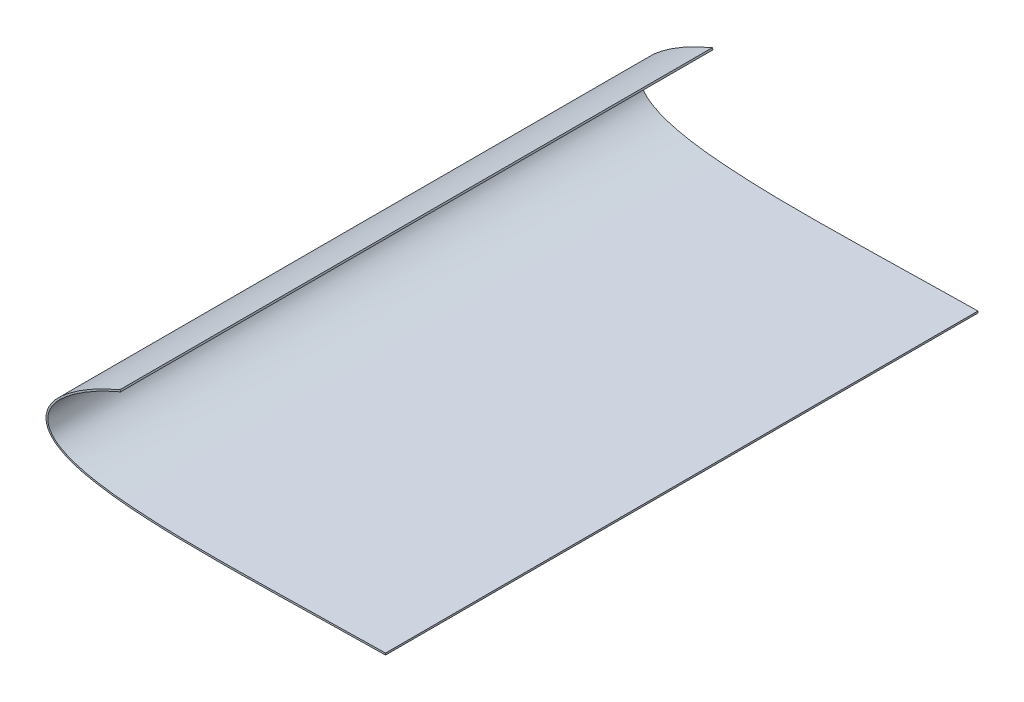
SolidWorks part; units mm, degrees
ref_plane "Front Plane" through (0, 0, 0) normal (0, 0, 1) x (1, 0, 0)
ref_plane "Top Plane" through (0, 0, 0) normal (0, 1, 0) x (1, 0, 0)
ref_plane "Right Plane" through (0, 0, 0) normal (1, 0, 0) x (0, 0, -1)
curve "ImportedCurve1"
curve "ImportedCurve2"
curve "ImportedCurve3"
curve "ImportedCurve4"
sketch "Sketch2" plane through (0, 0, 0) normal (0, 0, 1) x (1, 0, 0)
  line L0 (52.451, 54.1567) -> (52.2798, 54.6368) construction
  line L1 (130.5487, 26.5347) -> (130.5552, 26.0143) construction
  line L2 (52.451, 54.1567) -> (52.2798, 54.6368)
  line L3 (130.5487, 26.5347) -> (130.5552, 26.0143)
  spline S0 degree 3 poles (-987.7293, 2865.6111) (174.4953, 40.72) (99.2593, 76.5475) (48.7263, 53.0365) (46.1986, 51.7856) (43.8514, 50.5628) (41.7065, 49.2754) (39.7334, 48.0293) (37.966, 46.7509) (36.3543, 45.5543) (34.9506, 44.3247) (33.731, 43.1376) (32.6875, 41.9647) (31.87, 40.7951) (31.2049, 39.6569) (30.8086, 38.5196) (30.5236, 37.4345) (30.431, 36.3628) (30.615, 35.3293) (30.8928, 34.3178) (31.4496, 33.3932) (32.1507, 32.5234) (32.9767, 31.6506) (34.0717, 30.9441) (35.2743, 30.2147) (36.6607, 29.5586) (38.2299, 28.9796) (39.9603, 28.4092) (41.8621, 27.9077) (43.9308, 27.4768) (46.1431, 27.0545) (48.5261, 26.7119) (51.0446, 26.3949) (53.7227, 26.0665) (56.5512, 25.9162) (59.5208, 25.6697) (62.6353, 25.5643) (65.8829, 25.3781) (69.2727, 25.3117) (72.7876, 25.2447) (76.441, 25.2178) (80.208, 25.2059) (84.0996, 25.2543) (88.0934, 25.2344) (92.2095, 25.3673) (96.4279, 25.3705) (100.7574, 25.4491) (105.1745, 25.5547) (109.6916, 25.6471) (114.2949, 25.7362) (118.9982, 25.8022) (123.7865, 25.9376) (352.3969, 28.3633) (578.4156, 67.421) (965.6359, -2808.828) knots 7.819677 7.819677 7.819677 7.819677 14.172368 14.290637 14.400564 14.505491 14.603093 14.69595 14.781007 14.860667 14.932933 15.001195 15.06164 15.117978 15.169576 15.216705 15.259669 15.302009 15.342391 15.383062 15.425175 15.468584 15.515144 15.566223 15.621722 15.681368 15.746954 15.819191 15.896502 15.979092 16.068737 16.162461 16.263371 16.368582 16.481002 16.597802 16.720476 16.84899 16.981978 17.12087 17.264218 17.413488 17.565777 17.723889 17.885151 18.052109 18.222097 18.396578 18.573966 18.755717 18.940377 19.12953 19.321463 45.942438 45.942438 45.942438 45.942438 only from (52.2798, 54.6368) to (130.5552, 26.0143) construction
  spline S1 degree 3 poles (-1321.8961, 2697.7864) (516.5479, -150.4893) (208.1789, 122.5208) (48.5985, 52.4662) (45.1489, 50.7908) (39.5693, 47.3621) (37.2938, 45.7687) (33.6489, 42.4218) (32.1506, 40.6939) (30.974, 37.4872) (30.8417, 36.1863) (31.6369, 33.8106) (32.4947, 32.7613) (34.3648, 31.279) (35.3859, 30.7214) (37.4227, 29.7823) (38.5093, 29.4116) (41.8889, 28.3539) (44.2531, 27.8939) (49.0056, 27.1184) (51.4047, 26.8526) (58.6332, 26.2111) (63.4698, 25.9577) (73.1544, 25.7277) (77.9969, 25.7165) (92.7642, 25.8004) (102.664, 26.0308) (315.8317, 29.8318) (520.7382, 65.6519) (720.7895, -2880.4831) knots -6.087253 -6.087253 -6.087253 -6.087253 14.151211 14.151211 14.604184 14.604184 14.932416 14.932416 15.199765 15.199765 15.362932 15.362932 15.5261 15.5261 15.66286 15.66286 15.79962 15.79962 16.086125 16.086125 16.37263 16.37263 16.945639 16.945639 17.518648 17.518648 18.689255 18.689255 42.70224 42.70224 42.70224 42.70224 only from (52.451, 54.1567) to (130.5487, 26.5347) construction
  spline S2 degree 3 poles (52.2798, 54.6368) (51.9842, 54.5111) (50.7699, 53.9873) (48.7263, 53.0365) (46.1986, 51.7856) (43.8514, 50.5628) (41.7065, 49.2754) (39.7334, 48.0293) (37.966, 46.7509) (36.3543, 45.5543) (34.9506, 44.3247) (33.731, 43.1376) (32.6875, 41.9647) (31.87, 40.7951) (31.2049, 39.6569) (30.8086, 38.5196) (30.5236, 37.4345) (30.431, 36.3628) (30.615, 35.3293) (30.8928, 34.3178) (31.4496, 33.3932) (32.1507, 32.5234) (32.9767, 31.6506) (34.0717, 30.9441) (35.2743, 30.2147) (36.6607, 29.5586) (38.2299, 28.9796) (39.9603, 28.4092) (41.8621, 27.9077) (43.9308, 27.4768) (46.1431, 27.0545) (48.5261, 26.7119) (51.0446, 26.3949) (53.7227, 26.0665) (56.5512, 25.9162) (59.5208, 25.6697) (62.6353, 25.5643) (65.8829, 25.3781) (69.2727, 25.3117) (72.7876, 25.2447) (76.441, 25.2178) (80.208, 25.2059) (84.0996, 25.2543) (88.0934, 25.2344) (92.2095, 25.3673) (96.4279, 25.3705) (100.7574, 25.4491) (105.1745, 25.5547) (109.6916, 25.6471) (114.2949, 25.7362) (118.9982, 25.8022) (123.7865, 25.9376) (127.6521, 25.9786) (129.9161, 26.0063) (130.5552, 26.0143) knots 14.134429 14.134429 14.134429 14.134429 14.172368 14.290637 14.400564 14.505491 14.603093 14.69595 14.781007 14.860667 14.932933 15.001195 15.06164 15.117978 15.169576 15.216705 15.259669 15.302009 15.342391 15.383062 15.425175 15.468584 15.515144 15.566223 15.621722 15.681368 15.746954 15.819191 15.896502 15.979092 16.068737 16.162461 16.263371 16.368582 16.481002 16.597802 16.720476 16.84899 16.981978 17.12087 17.264218 17.413488 17.565777 17.723889 17.885151 18.052109 18.222097 18.396578 18.573966 18.755717 18.940377 19.12953 19.321463 19.396956 19.396956 19.396956 19.396956
  spline S3 degree 3 poles (52.451, 54.1567) (52.3312, 54.1046) (52.2116, 54.0523) (48.5985, 52.4662) (45.1489, 50.7908) (39.5693, 47.3621) (37.2938, 45.7687) (33.6489, 42.4218) (32.1506, 40.6939) (30.974, 37.4872) (30.8417, 36.1863) (31.6369, 33.8106) (32.4947, 32.7613) (34.3648, 31.279) (35.3859, 30.7214) (37.4227, 29.7823) (38.5093, 29.4116) (41.8889, 28.3539) (44.2531, 27.8939) (49.0056, 27.1184) (51.4047, 26.8526) (58.6332, 26.2111) (63.4698, 25.9577) (73.1544, 25.7277) (77.9969, 25.7165) (92.7642, 25.8004) (102.664, 26.0308) (118.5633, 26.3143) (124.5553, 26.4491) (130.5487, 26.5347) knots 14.135709 14.135709 14.135709 14.135709 14.151211 14.151211 14.604184 14.604184 14.932416 14.932416 15.199765 15.199765 15.362932 15.362932 15.5261 15.5261 15.66286 15.66286 15.79962 15.79962 16.086125 16.086125 16.37263 16.37263 16.945639 16.945639 17.518648 17.518648 18.689255 18.689255 19.396987 19.396987 19.396987 19.396987
extrude "Boss-Extrude1" add sketch "Sketch2" along normal blind 174.625
